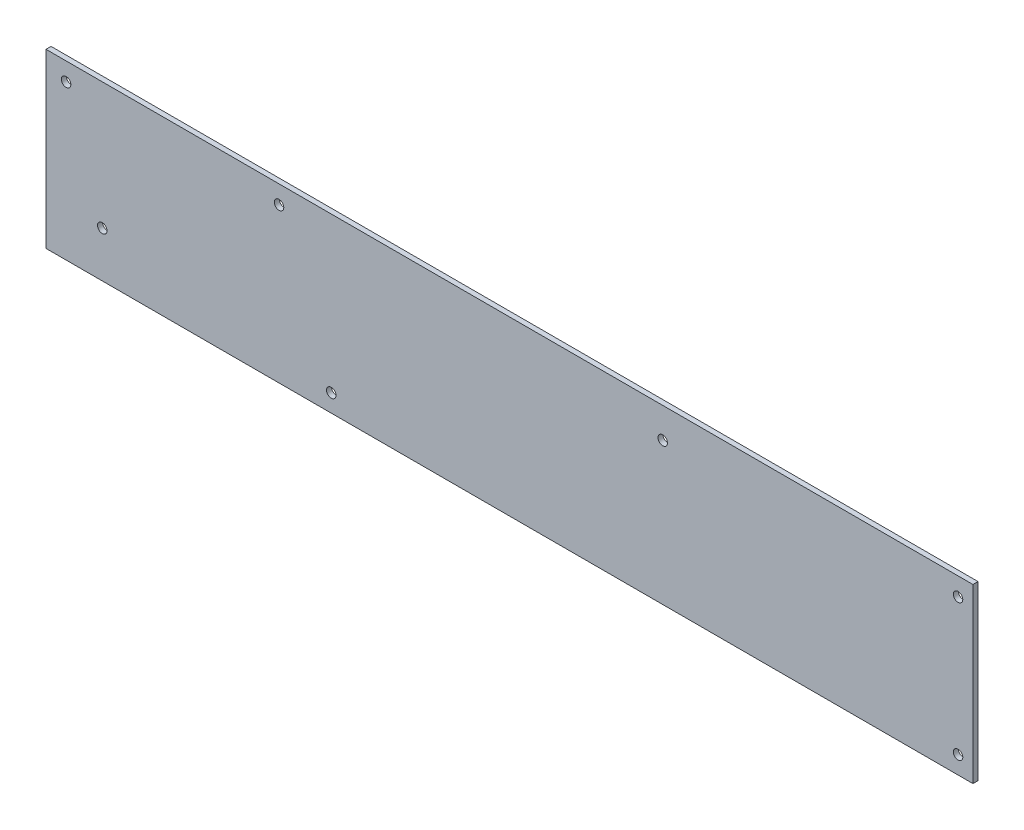
SolidWorks part; units mm, degrees
ref_plane "Front Plane" through (0, 0, 0) normal (0, 0, 1) x (1, 0, 0)
ref_plane "Top Plane" through (0, 0, 0) normal (0, 1, 0) x (1, 0, 0)
ref_plane "Right Plane" through (0, 0, 0) normal (1, 0, 0) x (0, 0, -1)
sketch "Sketch2" plane through (0, 0, 0) normal (0, 0, 1) x (1, 0, 0)
  line L1 (146.5, -27.26) -> (-146.5, -27.26)
  line L2 (146.5, -27.26) -> (146.5, 27.26)
  line L3 (146.5, 27.26) -> (-146.5, 27.26)
  line L4 (-146.5, -27.26) -> (-146.5, 27.26)
  line L5 (146.5, -27.26) -> (-146.5, 27.26) construction
  line L6 (146.5, 27.26) -> (-146.5, -27.26) construction
  point P0 (0, 0)
  dimension "D1" = 293
  dimension "D2" = 54.52
extrude "ExtrudedBase_PCB" add sketch "Sketch2" along normal blind 1.6
sketch "Sketch3" plane through (0, 0, 1.6) normal (0, 0, 1) x (1, 0, 0)
  line L0 (-146.5, 27.26) -> (-146.5, -27.26) construction
  line L2 (-146.5, -27.26) -> (146.5, -27.26) construction
  circle A0 centre (-140.15, 21.508) radius 1.5
  circle A1 centre (-72.84, 21.508) radius 1.5
  circle A2 centre (48.445, 17.698) radius 1.5
  circle A3 centre (141.79, 21.508) radius 1.5
  circle A4 centre (-128.72, -12.782) radius 1.5
  circle A5 centre (-56.33, -21.672) radius 1.5
  circle A6 centre (141.79, -21.672) radius 1.5
  dimension "D1" = 6.35
  dimension "D3" = 73.66
  dimension "D2" = 44.958
  dimension "D4" = 288.29
  dimension "D5" = 14.478
  dimension "D6" = 194.945
  dimension "D7" = 48.768
  dimension "D8" = 5.588
  dimension "D9" = 5.588
  dimension "D10" = 288.29
  dimension "D11" = 17.78
  dimension "D12" = 90.17
extrude "ExtrudedCut_MountingHoles" cut sketch "Sketch3" against normal through all
